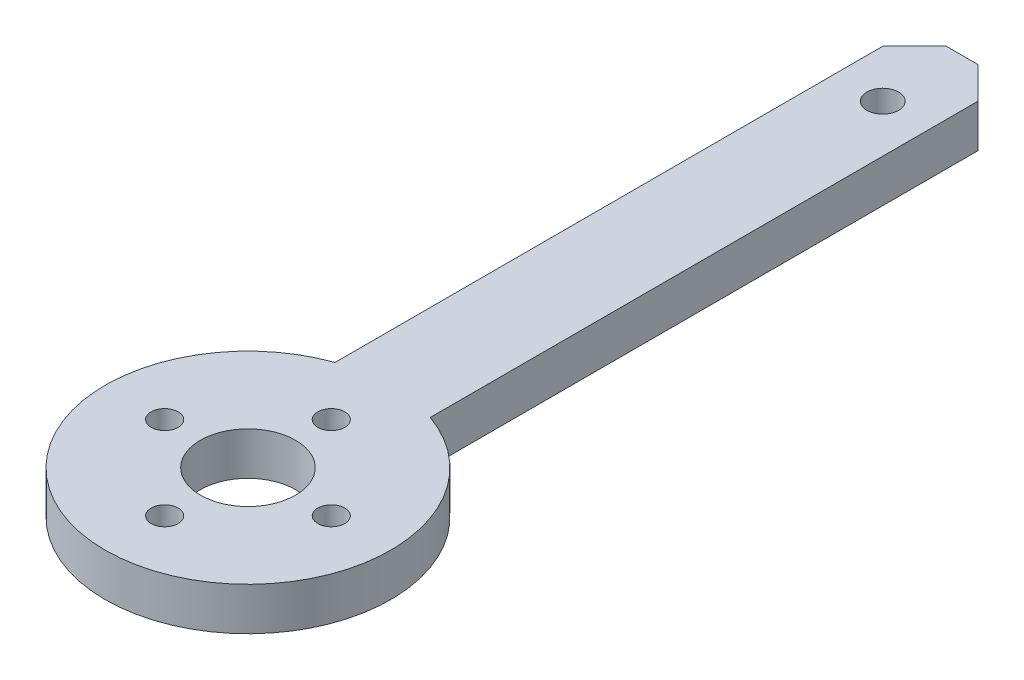
SolidWorks part; units mm, degrees
ref_plane "Front Plane" through (0, 0, 0) normal (0, 0, 1) x (1, 0, 0)
ref_plane "Top Plane" through (0, 0, 0) normal (0, 1, 0) x (1, 0, 0)
ref_plane "Right Plane" through (0, 0, 0) normal (1, 0, 0) x (0, 0, -1)
sketch "Sketch1" plane through (0, 0, 0) normal (0, 1, 0) x (1, 0, 0)
  circle A0 centre (0, 0) radius 18
  dimension "D1" = 36
extrude "Boss-Extrude2" add sketch "Sketch1" along normal blind 5.4
sketch "Sketch2" plane through (0, 0, 0) normal (0, 1, 0) x (1, 0, 0)
  line L0 (-2.75, 0) -> (2.75, 0) construction
  line L1 (-6, 0) -> (6, 0)
  line L2 (-6, 0) -> (-6, 90)
  line L3 (-6, 90) -> (6, 90)
  line L4 (6, 0) -> (6, 90)
  line L5 (0, 90) -> (0, 0) construction
  line L7 (-6, 45) -> (6, 45) construction
  line L8 (0, -2.75) -> (0, 2.75) construction
  point P12 (0, 45)
  dimension "D1" = 12
  dimension "D2" = 90
extrude "Boss-Extrude3" add sketch "Sketch2" along normal blind 5.4
sketch "Sketch3" plane through (0, 0, 0) normal (0, 1, 0) x (1, 0, 0)
  line L0 (0, 0) -> (10.5, 0) construction
  line L2 (-2.75, 0) -> (2.75, 0) construction
  circle A0 centre (10.5, 0) radius 1.7
  circle A4 centre (0, 0) radius 6
  circle A5 centre (0, -10.5) radius 1.7
  circle A6 centre (-10.5, 0) radius 1.7
  circle A7 centre (0, 10.5) radius 1.7
  point P15 (0, -2.4749)
  point P17 (0, 0)
  dimension "D3" = 3.4
  dimension "D5" = 12
  dimension "D2" = 10.5
  dimension "D1" = 4
extrude "Cut-Extrude1" cut sketch "Sketch3" along normal through all
chamfer "Chamfer1" distance 4 angle 45 2 edges at (-6, 2.7, -90) (6, 2.7, -90)
sketch "Sketch4" plane through (0, 5.4, 0) normal (0, 1, 0) x (1, 0, 0)
  line L0 (0, -2.97) -> (0, 2.97) construction
  circle A0 centre (0, 80) radius 2
  dimension "D1" = 4
  dimension "D2" = 80
extrude "Cut-Extrude2" cut sketch "Sketch4" against normal through all
equation "\"pin_circle_R\" = 27"
equation "\"ecc\" = 1.5"
equation "\"n_pins\" = 11"
equation "\"pin_d\" = 3"
equation "\"out_pin_R\" = 18.5"
equation "\"disc_clr\" = 0.1"
equation "\"seat_6803\" = 26.02"
equation "\"seat_6806\" = 42.1"
equation "\"disc_t\" = 5"
equation "\"out_hole_clr\" = 0.7"
equation "\"boss_17\" = 17.15"
equation "\"rotor_bolt_R\" = 10"
equation "\"m25_clr\" = 2.8"
equation "\"m25_head\" = 5"
equation "\"insert_hole\" = 4.4"
equation "\"csk\" = 0.6"
equation "\"peg_d\" = 3.0"
equation "\"plug_d\" = 8.6"
equation "\"peg_clr\" = 0.18"
equation "\"m3_clr\" = 3.4"
equation "\"m3_head\" = 6.2"
equation "\"pin_press\" = 3.2"
equation "\"pin_slip\" = 3.35"
equation "\"hub_30\" = 30.20"
equation "\"hub_short\" = 0.2"
equation "\"m3_tap\" = 2.8"
equation "\"rear_plate_t\" = 2"
equation "\"motor_ring\" = 40.4"
equation "\"plug_shaft_d\" = 8.8"
equation "\"D3@Sketch3\"=\"m3_clr\""
